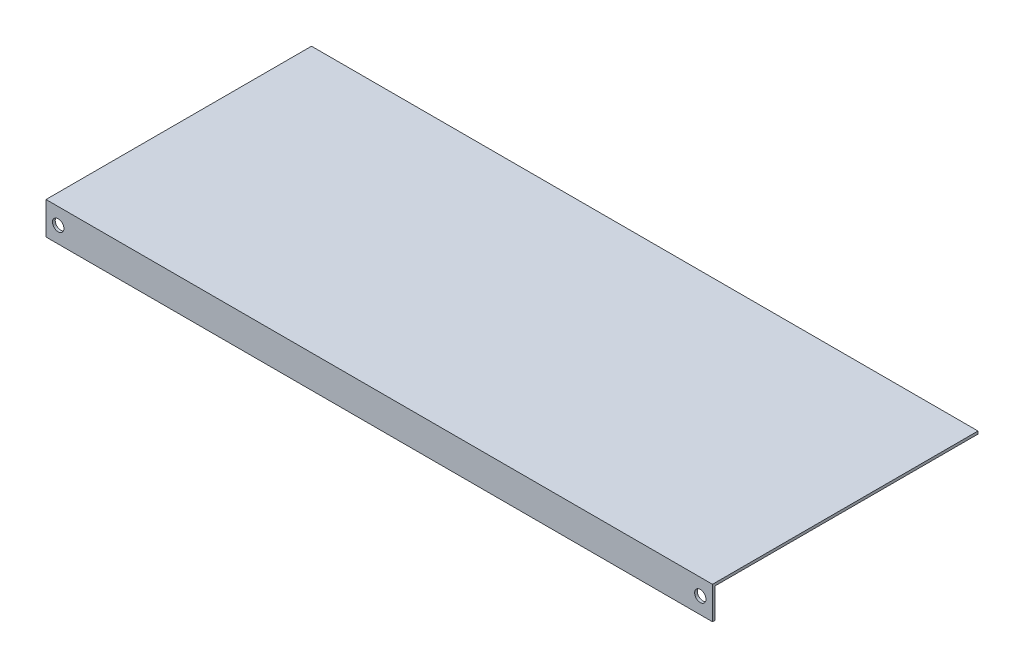
SolidWorks part; units mm, degrees
ref_plane "Спереди" through (0, 0, 0) normal (0, 0, 1) x (1, 0, 0)
ref_plane "Сверху" through (0, 0, 0) normal (0, 1, 0) x (1, 0, 0)
ref_plane "Справа" through (0, 0, 0) normal (1, 0, 0) x (0, 0, -1)
sketch "Эскиз1" plane through (0, 0, 0) normal (0, 1, 0) x (1, 0, 0)
  line L5 (-123, -49) -> (123, -49)
  line L6 (-123, -49) -> (-123, 49)
  line L7 (-123, 49) -> (123, 49)
  line L8 (123, -49) -> (123, 49)
  line L9 (-123, -49) -> (123, 49) construction
  line L10 (-123, 49) -> (123, -49) construction
  point P0 (0, 0)
  dimension "D1" = 246
  dimension "D2" = 98
extrude "Бобышка-Вытянуть1" add sketch "Эскиз1" along normal blind 1
sketch "Эскиз2" plane through (0, 0, 0) normal (0, -1, 0) x (1, 0, 0)
  line L0 (123, 49) -> (123, -49) construction
  line L1 (-123, 49) -> (123, 49)
  line L2 (-123, 49) -> (-123, 48)
  line L3 (-123, 48) -> (123, 48)
  line L4 (123, 49) -> (123, 48)
  dimension "D1" = 1
extrude "Бобышка-Вытянуть2" add sketch "Эскиз2" along normal blind 11
sketch "Эскиз3" plane through (0, 0, 49) normal (0, 0, 1) x (1, 0, 0)
  line L0 (0, 50.3944) -> (0, -50.3944) construction
  line L1 (-123, 1) -> (123, 1) construction
  line L6 (123, 1) -> (123, -11) construction
  point P2 (118.5, -5)
  point P8 (-118.5, -5)
  dimension "D1" = 6
  dimension "D2" = 4.5
hole_wizard "Сверло под метчик  спиральное M41" positions "Эскиз4" profile "Эскиз5" hole size "M4x0.7" standard "DIN" end condition through all
sketch "Эскиз4" plane through (0, 0, 49) normal (0, 0, 1) x (1, 0, 0)
  point P0 (118.5, -5)
  point P3 (-118.5, -5)
sketch "Эскиз5" plane through (118.5, -5, 49) normal (1, 0, 0) x (0, -1, 0)
  line L0 (0, 0) -> (0, 98)
  line L1 (0, 98) -> (2.1, 98)
  line L2 (2.1, 98) -> (2.1, 0)
  line L5 (2.1, 0) -> (0, 0)
  line L11 (0, -6.35) -> (0, 107.95) construction
  dimension "Диаметр сквозного отверстия" = 4.2
  dimension "Глубина сквозного отверстия" = 98
